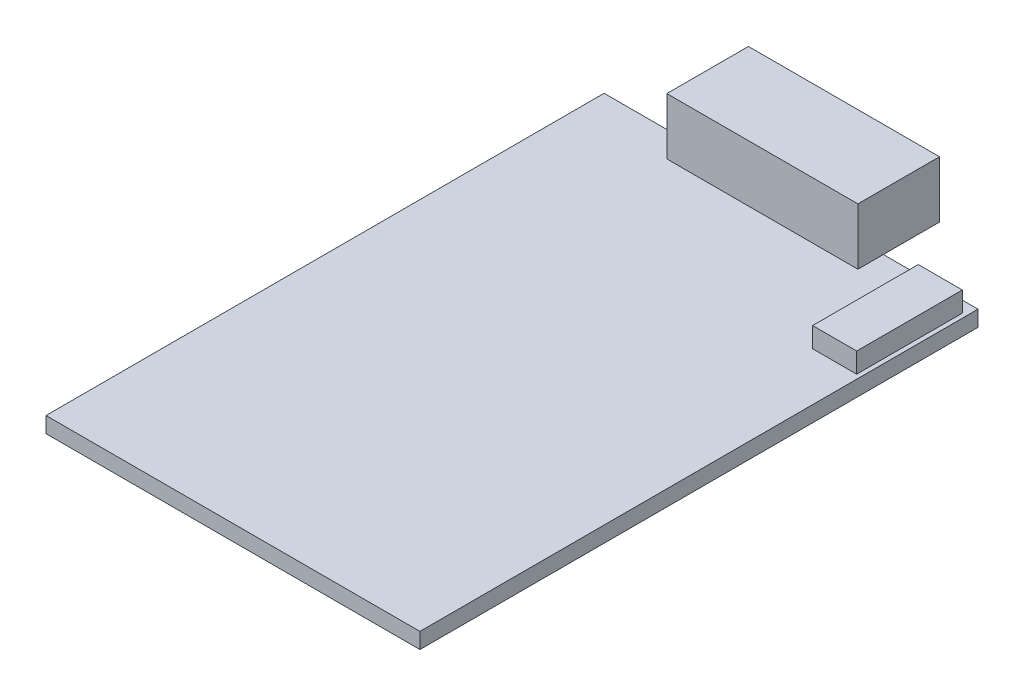
SolidWorks part; units mm, degrees
ref_plane "Front Plane" through (0, 0, 0) normal (0, 0, 1) x (1, 0, 0)
ref_plane "Top Plane" through (0, 0, 0) normal (0, 1, 0) x (1, 0, 0)
ref_plane "Right Plane" through (0, 0, 0) normal (1, 0, 0) x (0, 0, -1)
sketch "Sketch1" plane through (0, 0, 0) normal (0, 1, 0) x (1, 0, 0)
  line L1 (0, 0) -> (39.63, 0)
  line L2 (0, 0) -> (0, 59.15)
  line L3 (0, 59.15) -> (39.63, 59.15)
  line L4 (39.63, 0) -> (39.63, 59.15)
  dimension "D1" = 59.15
  dimension "D2" = 39.63
extrude "Boss-Extrude1" add sketch "Sketch1" along normal blind 1.67
sketch "Sketch2" plane through (0, 0, 0) normal (0, 1, 0) x (1, 0, 0)
  line L1 (9.35, 65.1) -> (29.6, 65.1)
  line L2 (9.35, 65.1) -> (9.35, 56.45)
  line L3 (9.35, 56.45) -> (29.6, 56.45)
  line L4 (29.6, 65.1) -> (29.6, 56.45)
  dimension "D1" = 20.25
  dimension "D2" = 8.65
  dimension "D3" = 9.35
  dimension "D4" = 56.45
extrude "Boss-Extrude2" add sketch "Sketch2" along normal blind 6 from surface at 1.67 starting at face at (19.815, 1.67, -29.575)
sketch "Sketch3" plane through (0, 0, 0) normal (0, 1, 0) x (1, 0, 0)
  line L2 (39.17, 57.95) -> (34.5, 57.95)
  line L3 (39.17, 57.95) -> (39.17, 46.75)
  line L4 (39.17, 46.75) -> (34.5, 46.75)
  line L5 (34.5, 57.95) -> (34.5, 46.75)
  point P0 (34.5, 35.9897)
  dimension "D1" = 4.67
  dimension "D2" = 11.2
  dimension "D3" = 34.5
  dimension "D4" = 46.75
extrude "Boss-Extrude3" add sketch "Sketch3" along normal blind 3.8
